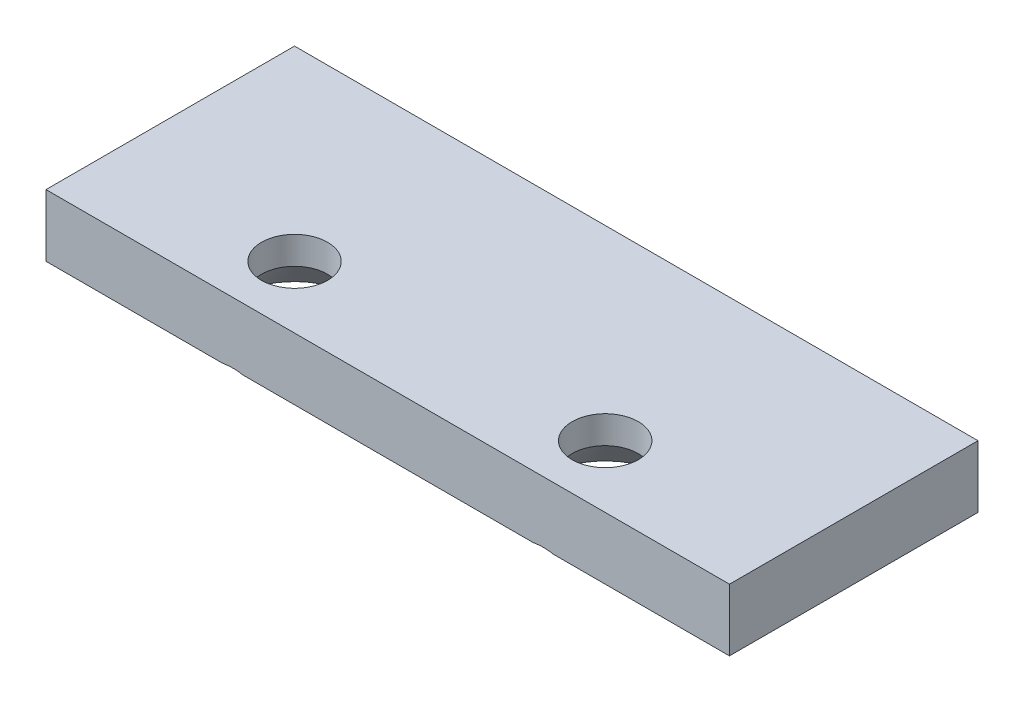
SolidWorks part; units mm, degrees
material "6061 Alloy"
ref_plane "Front Plane" through (0, 0, 0) normal (0, 0, 1) x (1, 0, 0)
ref_plane "Top Plane" through (0, 0, 0) normal (0, 1, 0) x (1, 0, 0)
ref_plane "Right Plane" through (0, 0, 0) normal (1, 0, 0) x (0, 0, -1)
sketch "Sketch1" plane through (0, 0, 0) normal (0, 1, 0) x (1, 0, 0)
  line L1 (34.925, -12.7) -> (-34.925, -12.7)
  line L2 (34.925, -12.7) -> (34.925, 12.7)
  line L3 (34.925, 12.7) -> (-34.925, 12.7)
  line L4 (-34.925, -12.7) -> (-34.925, 12.7)
  line L5 (34.925, -12.7) -> (-34.925, 12.7) construction
  line L6 (34.925, 12.7) -> (-34.925, -12.7) construction
  point P0 (0, 0)
  dimension "D1" = 69.85
  dimension "D2" = 25.4
extrude "Boss-Extrude1" add sketch "Sketch1" along normal blind 6.35
hole_wizard "CSK for 1/4 Flat Head Machine Screw1" positions "Sketch2" profile "Sketch3" countersink size "1/4" standard "ANSI Inch"
sketch "Sketch2" plane through (0, 0, 0) normal (0, -1, 0) x (-1, 0, 0)
  line L0 (34.925, -12.7) -> (-34.925, -12.7) construction
  line L1 (34.925, 12.7) -> (34.925, -12.7) construction
  line L2 (-34.925, -12.7) -> (-34.925, 12.7) construction
  point P0 (15.875, -6.35)
  point P2 (-15.875, -6.35)
  dimension "D1" = 6.35
  dimension "D2" = 6.35
  dimension "D3" = 19.05
  dimension "D4" = 19.05
sketch "Sketch3" plane through (-15.875, 0, 6.35) normal (1, 0, 0) x (0, 0, -1)
  line L0 (0, 0) -> (0, 17.2698)
  line L1 (0, 17.2698) -> (3.3782, 15.24)
  line L2 (3.3782, 15.24) -> (3.3782, 3.5209)
  line L3 (3.3782, 3.5209) -> (6.4389, 0)
  line L5 (6.4389, 0) -> (0, 0)
  line L6 (-3.3782, 3.5209) -> (-6.4389, 0) construction
  line L10 (0, 17.2698) -> (-3.3782, 15.24) construction
  line L11 (0, -6.35) -> (0, 107.95) construction
  dimension "Hole Dia." = 6.7564
  dimension "Hole Depth" = 15.24
  dimension "Near C'Sink Dia." = 12.8778
  dimension "Near C'Sink Angle" = 82
  dimension "Drill Angle" = 118
